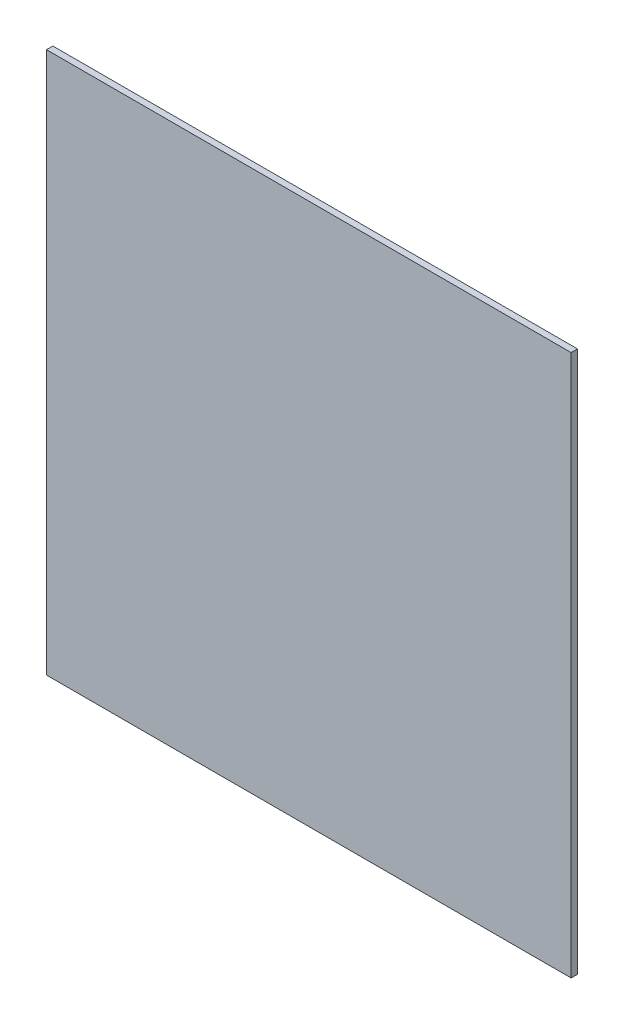
SolidWorks part; units mm, degrees
ref_plane "Plan de face" through (0, 0, 0) normal (0, 0, 1) x (1, 0, 0)
ref_plane "Plan de dessus" through (0, 0, 0) normal (0, 1, 0) x (1, 0, 0)
ref_plane "Plan de droite" through (0, 0, 0) normal (1, 0, 0) x (0, 0, -1)
sketch "Esquisse1" plane through (0, 0, 0) normal (0, 0, 1) x (1, 0, 0)
  line L1 (-123.75, -127.75) -> (123.75, -127.75)
  line L2 (-123.75, -127.75) -> (-123.75, 127.75)
  line L3 (-123.75, 127.75) -> (123.75, 127.75)
  line L4 (123.75, -127.75) -> (123.75, 127.75)
  line L5 (-123.75, -127.75) -> (123.75, 127.75) construction
  line L6 (-123.75, 127.75) -> (123.75, -127.75) construction
  point P0 (0, 0)
  dimension "D1" = 247.5
  dimension "D2" = 255.5
extrude "Boss.-Extru.1" add sketch "Esquisse1" along normal blind 3
